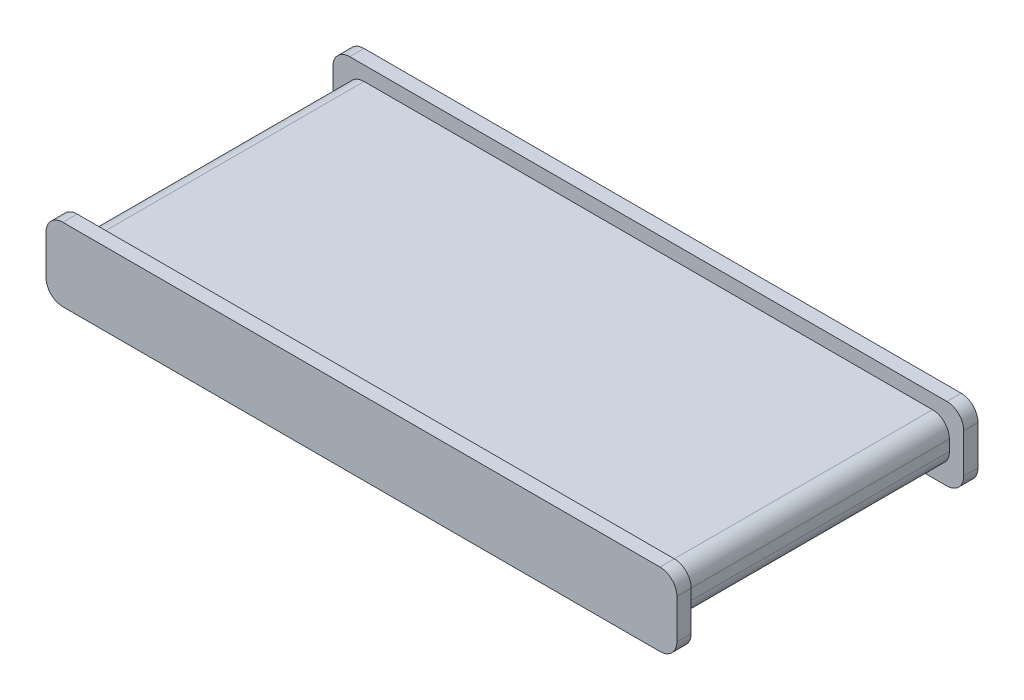
SolidWorks part; units mm, degrees
material "ABS"
ref_plane "X-Y Datum" through (0, 0, 0) normal (0, 0, 1) x (1, 0, 0)
ref_plane "X-Z Datum" through (0, 0, 0) normal (0, 1, 0) x (1, 0, 0)
ref_plane "Y-Z Datum" through (0, 0, 0) normal (1, 0, 0) x (0, 0, -1)
sketch "Sketch2" plane through (0, 0, 0) normal (0, 0, 1) x (1, 0, 0)
  line L6 (107, 7.9241) -> (0, 7.9241)
  line L7 (107, 7.9241) -> (107, 0)
  line L8 (107, 0) -> (0, 0)
  line L9 (0, 7.9241) -> (0, 0)
  dimension "D1" = 107
extrude "Boss-Extrude1" add sketch "Sketch2" along normal blind 48.42
fillet "Fillet1" radius 3 4 edges at (107, 7.9241, 24.21) (107, 0, 24.21) (0, 7.9241, 24.21) (0, 0, 24.21)
sketch "Sketch3" plane through (0, 0, 48.42) normal (0, 0, 1) x (1, 0, 0)
  line L0 (104, 7.9241) -> (3, 7.9241) construction
  line L1 (-2.54, -2.54) -> (109.54, -2.54)
  line L2 (-2.54, -2.54) -> (-2.54, 10.4641)
  line L3 (-2.54, 10.4641) -> (109.54, 10.4641)
  line L4 (109.54, -2.54) -> (109.54, 10.4641)
  line L5 (3, 0) -> (104, 0) construction
  line L6 (0, 4.9241) -> (0, 3) construction
  line L7 (107, 3) -> (107, 4.9241) construction
  dimension "D1" = 2.54
  dimension "D2" = 2.54
  dimension "D3" = 2.54
  dimension "D4" = 2.54
extrude "Boss-Extrude2" add sketch "Sketch3" along normal blind 2.54
sketch "Sketch4" plane through (0, 0, 0) normal (0, 0, -1) x (-1, 0, 0)
  line L1 (-109.54, 10.4641) -> (2.54, 10.4641)
  line L2 (-109.54, 10.4641) -> (-109.54, -2.54)
  line L3 (-109.54, -2.54) -> (2.54, -2.54)
  line L4 (2.54, 10.4641) -> (2.54, -2.54)
extrude "Boss-Extrude3" add sketch "Sketch4" along normal blind 2.54
fillet "Fillet2" radius 3 8 edges at (-2.54, -2.54, -1.27) (-2.54, 10.4641, -1.27) (109.54, 10.4641, -1.27) (109.54, -2.54, -1.27) (109.54, 10.4641, 49.69) (109.54, -2.54, 49.69) (-2.54, 10.4641, 49.69) (-2.54, -2.54, 49.69)
